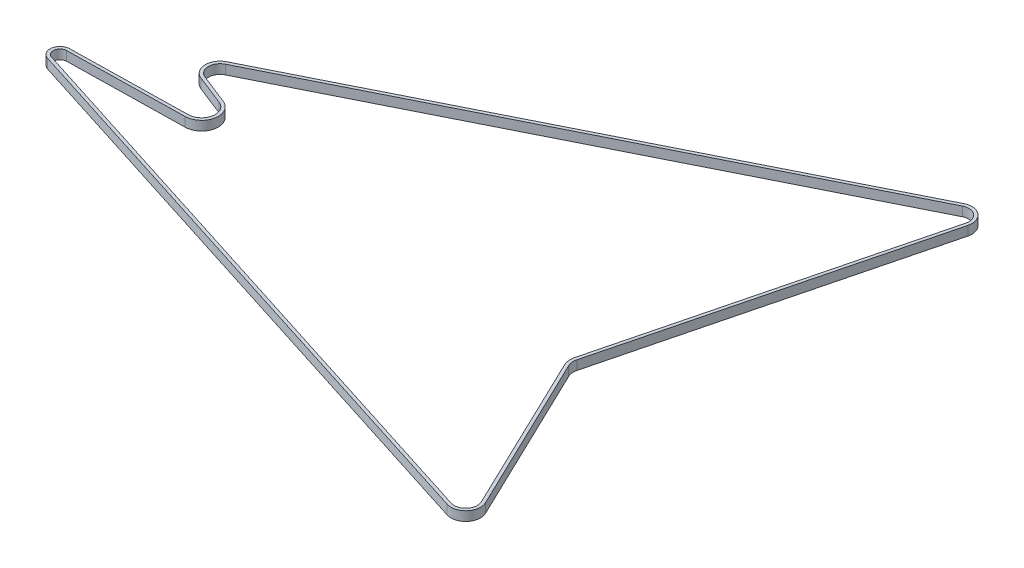
SolidWorks part; units mm, degrees
ref_plane "Front Plane" through (0, 0, 0) normal (0, 0, 1) x (1, 0, 0)
ref_plane "Top Plane" through (0, 0, 0) normal (0, 1, 0) x (1, 0, 0)
ref_plane "Right Plane" through (0, 0, 0) normal (1, 0, 0) x (0, 0, -1)
sketch "Sketch1" plane through (0, 86.8, 0) normal (0, 1, 0) x (1, 0, 0)
  line L0 (-160.9741, -6.978) -> (-141.5171, -14.6435) construction
  line L1 (-145.2593, -35.3934) -> (-220.2307, -36.7757) construction
  line L2 (-221.4761, -45.3192) -> (155.9516, -165.3721) construction
  line L3 (115.3116, -51.658) -> (164.9844, -154.9752) construction
  line L4 (165.4948, 156.3811) -> (114.5799, -44.3571) construction
  line L5 (-161.5791, 6.7082) -> (154.8709, 164.9332) construction
  line L6 (-160.9741, -6.978) -> (-141.5171, -14.6435)
  line L7 (-145.2593, -35.3934) -> (-220.2307, -36.7757)
  line L8 (-221.4761, -45.3192) -> (155.9516, -165.3721)
  line L9 (115.3116, -51.658) -> (164.9844, -154.9752)
  line L10 (165.4948, 156.3811) -> (114.5799, -44.3571)
  line L11 (-161.5791, 6.7082) -> (154.8709, 164.9332)
  arc A0 (-161.5791, 6.7082) -> (-160.9741, -6.978) centre (-158.225, 0) ccw construction
  arc A1 (-145.2593, -35.3934) -> (-141.5171, -14.6435) centre (-145.4575, -24.6453) ccw construction
  arc A2 (-220.2307, -36.7757) -> (-221.4761, -45.3192) centre (-220.15, -41.15) ccw construction
  arc A3 (155.9516, -165.3721) -> (164.9844, -154.9752) centre (158.225, -158.225) ccw construction
  arc A4 (114.5799, -44.3571) -> (115.3116, -51.658) centre (125, -47) ccw construction
  arc A5 (165.4948, 156.3811) -> (154.8709, 164.9332) centre (158.225, 158.225) ccw construction
  arc A6 (-161.5791, 6.7082) -> (-160.9741, -6.978) centre (-158.225, 0) ccw
  arc A7 (-145.2593, -35.3934) -> (-141.5171, -14.6435) centre (-145.4575, -24.6453) ccw
  arc A8 (-220.2307, -36.7757) -> (-221.4761, -45.3192) centre (-220.15, -41.15) ccw
  arc A9 (155.9516, -165.3721) -> (164.9844, -154.9752) centre (158.225, -158.225) ccw
  arc A10 (114.5799, -44.3571) -> (115.3116, -51.658) centre (125, -47) ccw
  arc A11 (165.4948, 156.3811) -> (154.8709, 164.9332) centre (158.225, 158.225) ccw
extrude "Extrude-Thin1" add sketch "Sketch1" along normal blind 6 thin
